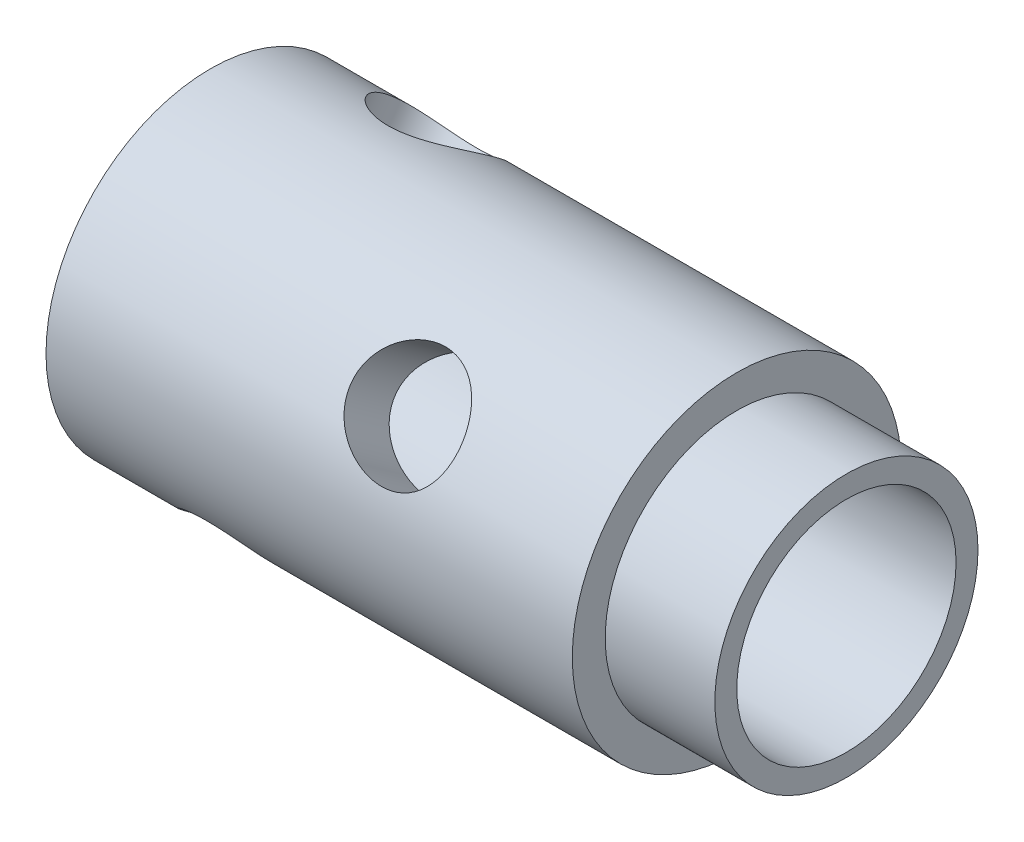
SolidWorks part; units mm, degrees
material "6061-T6 (SS)"
ref_plane "Front Plane" through (0, 0, 0) normal (0, 0, 1) x (1, 0, 0)
ref_plane "Top Plane" through (0, 0, 0) normal (0, 1, 0) x (1, 0, 0)
ref_plane "Right Plane" through (0, 0, 0) normal (1, 0, 0) x (0, 0, -1)
sketch "Sketch2" plane through (0, 0, 0) normal (0, 0, 1) x (1, 0, 0)
  line L0 (0, 6) -> (-5, 6)
  line L1 (-5, 7.5) -> (-29, 7.5)
  line L2 (-29, 7.5) -> (-29, 5)
  line L3 (-5, 6) -> (-5, 7.5)
  line L4 (0, 0) -> (-14317.1336, 0) construction
  line L5 (-29, 5) -> (0, 5)
  line L6 (0, 5) -> (0, 6)
  line L7 (0, 0) -> (0, 17.3729) construction
  point P11 (0, 5.5)
  dimension "D1" = 5
  dimension "D2" = 6
  dimension "D3" = 5
  dimension "D4" = 24
  dimension "D5" = 7.5
revolve "Revolve1" add sketch "Sketch2" angle 360 about L4
sketch "Sketch3" plane through (-120.7501, -67.4536, 42.3514) normal (0, -0.5839, -0.8119) x (-0.5094, 0.6986, -0.5024)
  circle A0 centre (14.0254, 132.3536) radius 2.5
sketch "Sketch4" plane through (-120.7501, 87.2435, 112.7488) normal (0, 0.8119, -0.5839) x (0.8562, 0.3017, 0.4195)
  circle A0 centre (10.0818, 172.4881) radius 2.5
extrude "Cut-Extrude1" cut sketch "Sketch4" against normal through all both and the other way through all contours A0
extrude "Cut-Extrude2" cut sketch "Sketch3" against normal through all both and the other way through all contours A0
